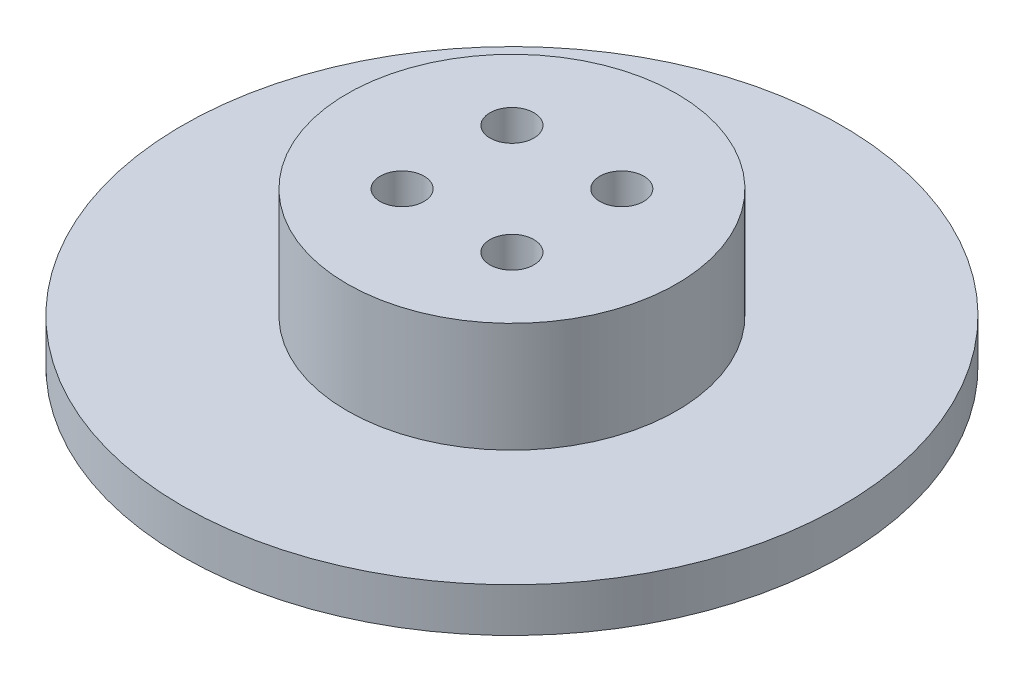
SolidWorks part; units mm, degrees
ref_plane "Front Plane" through (0, 0, 0) normal (0, 0, 1) x (1, 0, 0)
ref_plane "Top Plane" through (0, 0, 0) normal (0, 1, 0) x (1, 0, 0)
ref_plane "Right Plane" through (0, 0, 0) normal (1, 0, 0) x (0, 0, -1)
sketch "Sketch1" plane through (0, 0, 0) normal (0, 1, 0) x (1, 0, 0)
  circle A0 centre (0, 0) radius 30
  dimension "D1" = 60
extrude "Boss-Extrude1" add sketch "Sketch1" along normal blind 4
sketch "Sketch2" plane through (0, 4, 0) normal (0, 1, 0) x (1, 0, 0)
  circle A0 centre (0, 0) radius 15
  dimension "D1" = 30
extrude "Boss-Extrude2" add sketch "Sketch2" along normal blind 10
sketch "Sketch3" plane through (0, 0, 0) normal (0, -1, 0) x (1, 0, 0)
  line L0 (10.5, 0) -> (-10.5, 0) construction
  line L1 (-21, 0) -> (-30, 0) construction
  line L2 (-10.5, 0) -> (-21, 0) construction
  arc A3 (-10.5, 0) -> (10.5, 0) centre (0, 0) ccw construction
  circle A4 centre (0, 0) radius 30 construction
  arc A5 (-18.375, -10.1666) -> (-18.375, 10.1666) centre (-21, 0) ccw construction
  arc A6 (10.5, 0) -> (-10.5, 0) centre (0, 0) ccw construction
  arc A7 (-21, 0) -> (-18.375, -10.1666) centre (0, 0) ccw construction
  arc A8 (-18.375, -10.1666) -> (-18.375, 10.1666) centre (0, 0) ccw construction
  arc A9 (-18.375, 10.1666) -> (-21, 0) centre (0, 0) ccw construction
  arc A10 (-18.375, 10.1666) -> (-18.375, -10.1666) centre (-21, 0) ccw construction
  circle A11 centre (-21, 0) radius 3
  circle A12 centre (0, 21) radius 3
  circle A13 centre (21, 0) radius 3
  circle A14 centre (0, -21) radius 3
  point P22 (0, 0)
  dimension "D1" = 21
  dimension "D2" = 21
  dimension "D3" = 6
  dimension "D4" = 4
extrude "Boss-Extrude3" add sketch "Sketch3" along normal blind 4
sketch "Sketch4" plane through (0, 14, 0) normal (0, 1, 0) x (1, 0, 0)
  line L0 (-15, 0) -> (-5, 0) construction
  line L1 (0, 15) -> (0, 5) construction
  line L2 (0, 5) -> (-5, 5) construction
  line L3 (5, -5) -> (0, -5) construction
  line L4 (5, 0) -> (5, 5) construction
  line L5 (5, 5) -> (0, 5) construction
  line L6 (-5, 0) -> (-5, 5) construction
  line L7 (5, -5) -> (0, 0) construction
  line L8 (5, 5) -> (0, 0) construction
  line L9 (0, 0) -> (-5, 5) construction
  line L10 (-5, 0) -> (0, 0) construction
  line L11 (0, 0) -> (5, 0) construction
  line L12 (-5, -5) -> (-5, 0) construction
  line L13 (0, 0) -> (-5, -5) construction
  line L14 (0, -5) -> (-5, -5) construction
  line L15 (0, -5) -> (0, -15) construction
  line L16 (5, -5) -> (5, 0) construction
  line L17 (5, 0) -> (15, 0) construction
  line L18 (0, 5) -> (0, 0) construction
  line L19 (0, 0) -> (0, -5) construction
  circle A0 centre (0, 0) radius 15 construction
  circle A1 centre (-5, 5) radius 2
  circle A2 centre (5, 5) radius 2
  circle A3 centre (5, -5) radius 2
  circle A4 centre (-5, -5) radius 2
  dimension "D1" = 30
  dimension "D4" = 4
  dimension "D2" = 10
  dimension "D3" = 10
extrude "Cut-Extrude1" cut sketch "Sketch4" against normal blind 4
